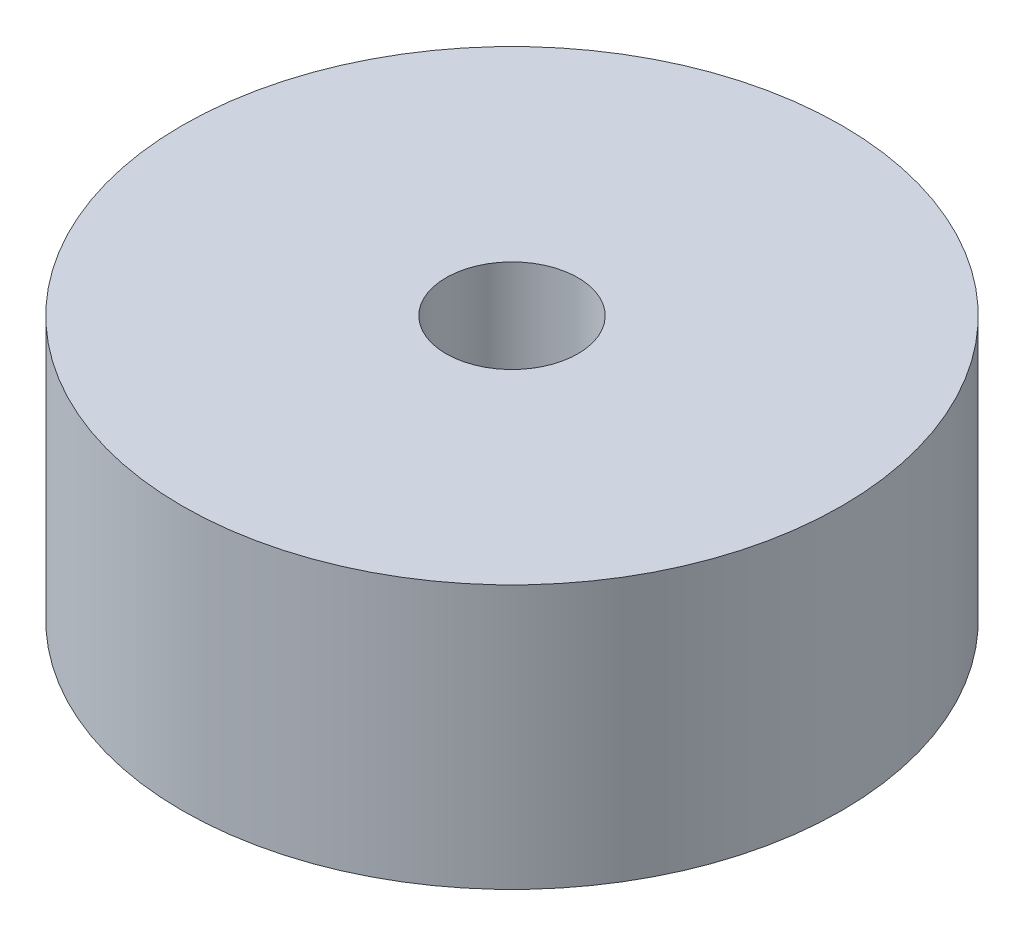
SolidWorks part; units mm, degrees
ref_plane "Plan de face" through (0, 0, 0) normal (0, 0, 1) x (1, 0, 0)
ref_plane "Plan de dessus" through (0, 0, 0) normal (0, 1, 0) x (1, 0, 0)
ref_plane "Plan de droite" through (0, 0, 0) normal (1, 0, 0) x (0, 0, -1)
sketch "Esquisse1" plane through (0, 0, 0) normal (0, 1, 0) x (1, 0, 0)
  circle A0 centre (0, 0) radius 15
extrude "Extrusion1" add sketch "Esquisse1" along normal blind 12
sketch "Esquisse2" plane through (0, 12, 0) normal (0, 1, 0) x (-1, 0, 0)
  circle A0 centre (0, 0) radius 3
extrude "Extrusion2" cut sketch "Esquisse2" against normal through all
